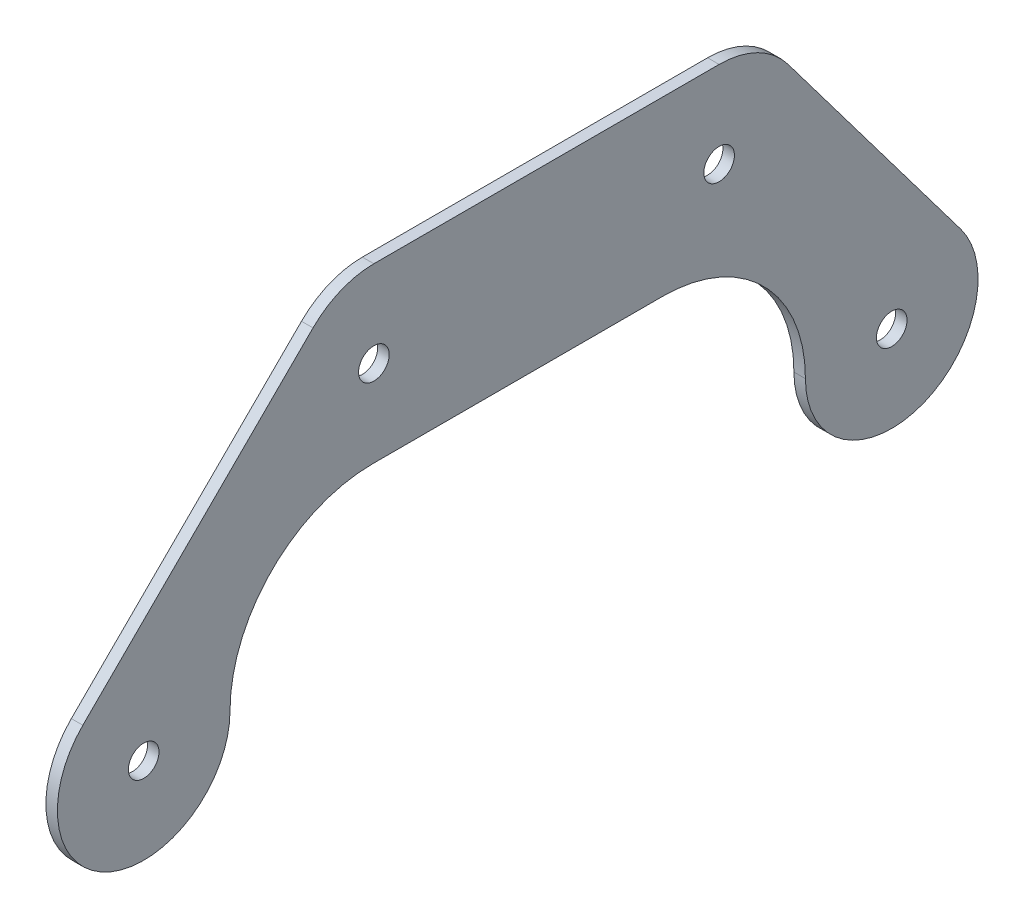
SolidWorks part; units mm, degrees
ref_plane "Front" through (0, 0, 0) normal (0, 0, 1) x (1, 0, 0)
ref_plane "Top" through (0, 0, 0) normal (0, 1, 0) x (1, 0, 0)
ref_plane "Right" through (0, 0, 0) normal (1, 0, 0) x (0, 0, -1)
sketch "Sketch1" plane through (0, 0, 0) normal (1, 0, 0) x (0, 0, -1)
  line L0 (-13.4366, 13.5041) -> (37.3634, 64.0501)
  line L1 (50.8, 69.596) -> (127, 69.596)
  line L2 (142.2124, 62.0127) -> (180.3124, 11.4667)
  line L3 (50.546, 31.496) -> (114.554, 31.496)
  arc A4 (-13.4366, 13.5041) -> (19.05, 0) centre (0, 0) ccw
  arc A5 (50.8, 69.596) -> (37.3634, 64.0501) centre (50.8, 50.546) ccw
  arc A6 (142.2124, 62.0127) -> (127, 69.596) centre (127, 50.546) ccw
  arc A7 (146.05, 0) -> (180.3124, 11.4667) centre (165.1, 0) ccw
  circle A8 centre (165.1, 0) radius 16.8275 construction
  circle A9 centre (127, 50.546) radius 16.8275 construction
  circle A10 centre (50.8, 50.546) radius 16.8275 construction
  arc A11 (50.546, 31.496) -> (19.05, 0) centre (50.546, 0) ccw
  arc A12 (146.05, 0) -> (114.554, 31.496) centre (114.554, 0) ccw
  dimension "D1" = 38.1
extrude "Boss-Extrude1" add sketch "Sketch1" along normal blind 2.54 contours A4 A11 L3 A12 A7 L2 A6 L1 A5 L0
hole_wizard "1/4 Clearance Hole1" positions "Sketch2" profile "Sketch3" hole size "1/4" standard "ANSI Inch" end condition through all
sketch "Sketch2" plane through (2.54, 0, 0) normal (1, 0, 0) x (0, 0, -1)
  arc A0 (50.8, 69.596) -> (37.3634, 64.0501) centre (50.8, 50.546) ccw construction
  arc A1 (142.2124, 62.0127) -> (127, 69.596) centre (127, 50.546) ccw construction
  arc A2 (146.05, 0) -> (180.3124, 11.4667) centre (165.1, 0) ccw construction
  point P0 (50.8, 50.546)
  point P2 (127, 50.546)
  point P4 (165.1, 0)
  point P6 (0, 0)
sketch "Sketch3" plane through (2.54, 50.546, -50.8) normal (0, 1, 0) x (0, 0, -1)
  line L0 (0, 0) -> (0, 2.54)
  line L1 (0, 2.54) -> (3.3782, 2.54)
  line L2 (3.3782, 2.54) -> (3.3782, 0)
  line L5 (3.3782, 0) -> (0, 0)
  line L11 (0, -6.35) -> (0, 107.95) construction
  dimension "Thru Hole Dia." = 6.7564
  dimension "Thru Hole Depth" = 2.54
hole_wizard "#8 Clearance Hole2" positions "Sketch5" profile "Sketch4" hole size "#8" standard "ANSI Inch"
sketch "Sketch5" plane through (2.54, 0, 0) normal (1, 0, 0) x (0, 0, -1)
  line L4 (157.7511, 18.1892) -> (142.4622, 38.4724)
  line L6 (11.9184, 20.8166) -> (20.9211, 29.7744) construction
  line L7 (20.9211, 29.7744) -> (29.9239, 38.7321) construction
  line L9 (50.8, 50.546) -> (76.2, 50.546)
  line L13 (0, 0) -> (50.8, 50.546) construction
  line L14 (76.2, 50.546) -> (88.9, 50.546)
  line L15 (88.9, 50.546) -> (101.6, 50.546)
  line L16 (101.6, 50.546) -> (127, 50.546)
  line L17 (20.9211, 29.7744) -> (25.4, 25.273) construction
  line L19 (127, 50.546) -> (165.1, 0)
  line L21 (150.1066, 28.3308) -> (146.05, 25.273)
  point P1 (76.2, 50.546)
  point P3 (88.9, 50.546)
  point P5 (101.6, 50.546)
  point P7 (29.9239, 38.7321)
  point P9 (20.9211, 29.7744)
  point P11 (11.9184, 20.8166)
  point P13 (142.4622, 38.4724)
  point P15 (150.1066, 28.3308)
  point P17 (157.7511, 18.1892)
  point P89 (146.05, 25.273)
  dimension "D1" = 6.35
  dimension "D2" = 12.7
  dimension "D3" = 25.4
  dimension "D4" = 5.08
sketch "Sketch4" plane through (2.54, 50.546, -76.2) normal (0, 1, 0) x (0, 0, -1)
  line L0 (0, 0) -> (0, 3.8897)
  line L1 (0, 3.8897) -> (2.2479, 2.539)
  line L2 (2.2479, 2.539) -> (2.2479, 0)
  line L5 (2.2479, 0) -> (0, 0)
  line L10 (0, 3.8897) -> (-2.2479, 2.539) construction
  line L11 (0, -6.35) -> (0, 107.95) construction
  dimension "Hole Dia." = 4.4958
  dimension "Hole Depth" = 2.539
  dimension "Drill Angle" = 118
